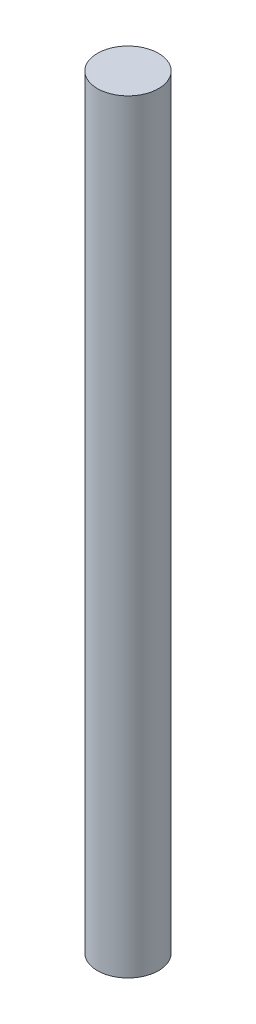
SolidWorks part; units mm, degrees
ref_plane "Front Plane" through (0, 0, 0) normal (0, 0, 1) x (1, 0, 0)
ref_plane "Top Plane" through (0, 0, 0) normal (0, 1, 0) x (1, 0, 0)
ref_plane "Right Plane" through (0, 0, 0) normal (1, 0, 0) x (0, 0, -1)
sketch "Sketch1" plane through (0, 0, 0) normal (0, 1, 0) x (1, 0, 0)
  circle A0 centre (0, 0) radius 0.5
  dimension "D1" = 1
extrude "Boss-Extrude1" add sketch "Sketch1" along normal blind 12.5
